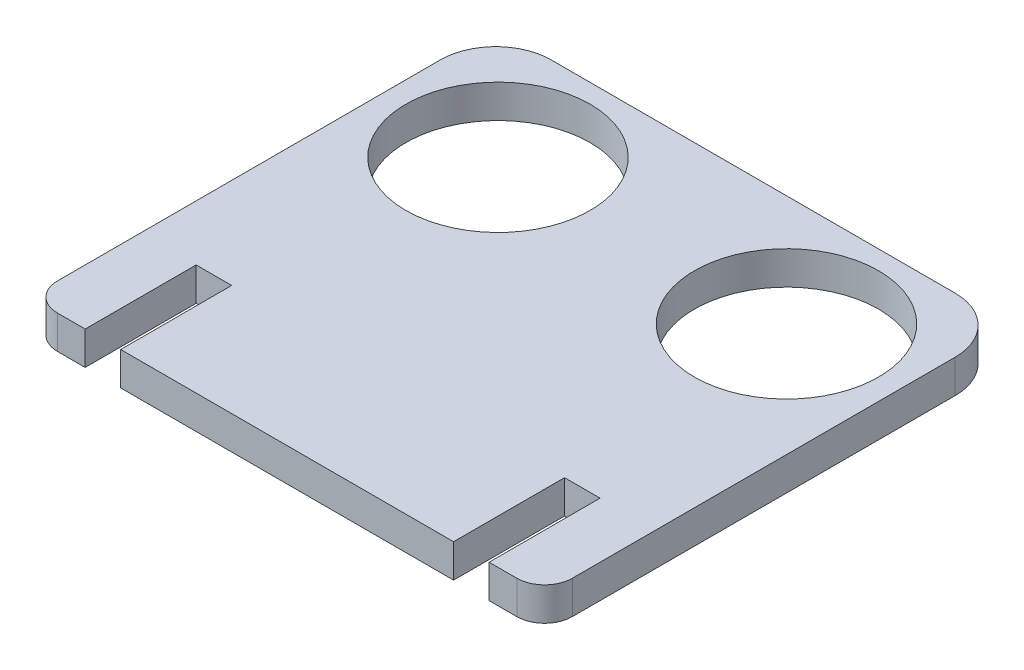
SolidWorks part; units mm, degrees
ref_plane "Front" through (0, 0, 0) normal (0, 0, 1) x (1, 0, 0)
ref_plane "Top" through (0, 0, 0) normal (0, 1, 0) x (1, 0, 0)
ref_plane "Right" through (0, 0, 0) normal (1, 0, 0) x (0, 0, -1)
sketch "草图1" plane through (0, 0, 0) normal (0, 1, 0) x (1, 0, 0)
  line L0 (15, 12) -> (23.2, 12) construction
  line L1 (-15, 12) -> (15, 12) construction
  line L2 (-15, 0) -> (-15, -10)
  line L3 (-15, -10) -> (15, -10)
  line L4 (15, 0) -> (15, -10)
  line L5 (0, -10) -> (0, 12) construction
  line L6 (-15, 0) -> (15, 0) construction
  line L7 (23.2, 12) -> (23.2, -7.5)
  line L8 (20.7, -10) -> (18.2, -10)
  line L9 (18.2, -10) -> (18.2, 0)
  line L10 (18.2, 0) -> (15, 0)
  line L11 (-18.2, 0) -> (-15, 0)
  line L12 (-18.2, -10) -> (-18.2, 0)
  line L13 (-20.7, -10) -> (-18.2, -10)
  line L14 (-23.2, 12) -> (-23.2, -7.5)
  line L15 (-15, 12) -> (-23.2, 12) construction
  line L16 (23.2, 12) -> (23.2, 27)
  line L17 (18.2, 32) -> (-18.2, 32)
  line L18 (-23.2, 27) -> (-23.2, 12)
  arc A2 (23.2, -7.5) -> (20.7, -10) centre (20.7, -7.5) cw
  arc A4 (-23.2, -7.5) -> (-20.7, -10) centre (-20.7, -7.5) ccw
  circle A5 centre (13, 22) radius 8.3
  circle A6 centre (-13, 22) radius 8.3
  arc A7 (-23.2, 27) -> (-18.2, 32) centre (-18.2, 27) cw
  arc A8 (23.2, 27) -> (18.2, 32) centre (18.2, 27) ccw
  point P0 (0, 0)
  point P17 (23.2, -10)
  point P30 (23.2, 32)
  dimension "D5" = 10
  dimension "D9" = 10
  dimension "D10" = 16.6
  dimension "D11" = 2.5
  dimension "D8" = 13
  dimension "D12" = 5
  dimension "D1" = 30
  dimension "D2" = 22
  dimension "D3" = 3.2
  dimension "D4" = 5
  dimension "D6" = 12
  dimension "D7" = 20
extrude "凸台-拉伸1" add sketch "草图1" along normal blind 3
